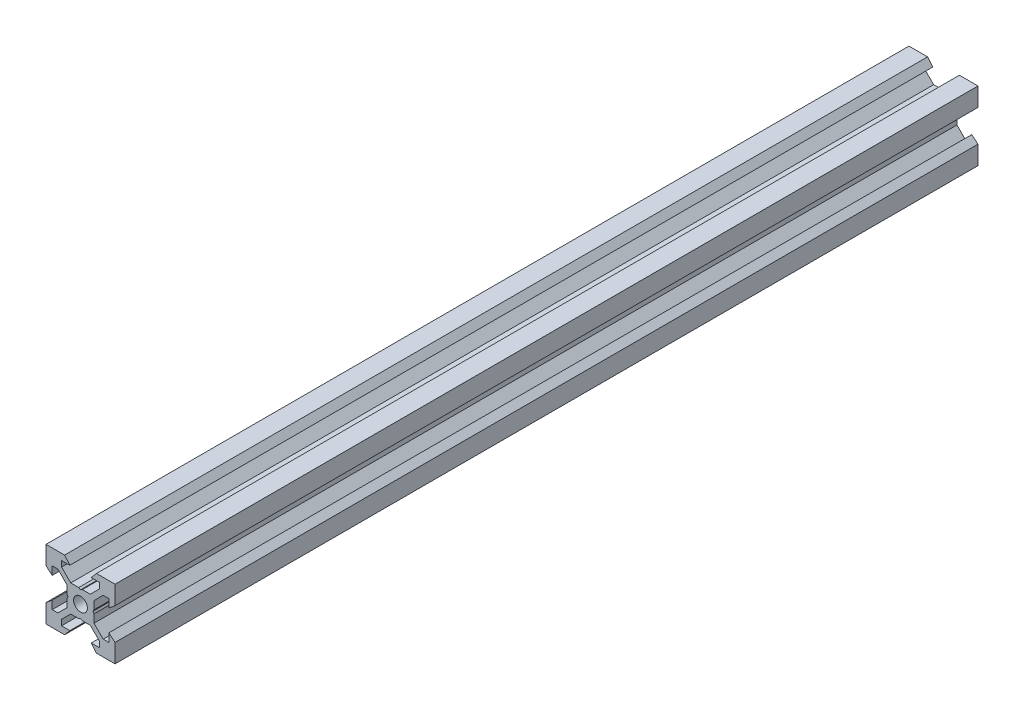
SolidWorks part; units mm, degrees
material "6063-O"
ref_plane "Front Plane" through (0, 0, 0) normal (0, 0, 1) x (1, 0, 0)
ref_plane "Top Plane" through (0, 0, 0) normal (0, 1, 0) x (1, 0, 0)
ref_plane "Right Plane" through (0, 0, 0) normal (1, 0, 0) x (0, 0, -1)
sketch "Sketch1" plane through (0, 0, 0) normal (0, 0, 1) x (1, 0, 0)
  line L0 (10, 10) -> (4.6104, 10) construction
  line L1 (10, 10) -> (10, 4.6104) construction
  line L2 (10, -10) -> (10, -4.6104) construction
  line L3 (10, -10) -> (4.6104, -10) construction
  line L4 (10, 10) -> (10, 4.6104)
  line L5 (6.5607, 5.5) -> (8.2, 5.5)
  line L6 (5.5, 8.2) -> (5.5, 6.5607)
  line L7 (10, 10) -> (4.6104, 10)
  line L8 (10, 10) -> (10, 4.6104)
  line L9 (6.5607, 5.5) -> (3.9, 2.8393)
  line L10 (5.5, 6.5607) -> (2.8393, 3.9)
  line L11 (10, 4.6104) -> (8.2, 3.1)
  line L12 (4.6104, 10) -> (3.1, 8.2)
  line L13 (8.2, 3.1) -> (8.2, 5.5)
  line L14 (3.1, 8.2) -> (5.5, 8.2)
  line L15 (-6.5607, 5.5) -> (-8.2, 5.5)
  line L16 (6.5607, -5.5) -> (8.2, -5.5)
  line L17 (3.1, -8.2) -> (5.5, -8.2)
  line L18 (8.2, -3.1) -> (8.2, -5.5)
  line L19 (4.6104, -10) -> (3.1, -8.2)
  line L20 (10, -4.6104) -> (8.2, -3.1)
  line L21 (0.5196, -3.9) -> (0, -3.6)
  line L22 (0.5196, 3.9) -> (0, 3.6)
  line L23 (3.6, 0) -> (3.9, -0.5196)
  line L24 (3.9, 0.5196) -> (3.6, 0)
  line L25 (3.9, 0.5196) -> (3.9, 2.8393)
  line L26 (2.8393, 3.9) -> (0.5196, 3.9)
  line L27 (3.9, -2.8393) -> (3.9, -0.5196)
  line L28 (2.8393, -3.9) -> (0.5196, -3.9)
  line L29 (5.5, -6.5607) -> (2.8393, -3.9)
  line L30 (6.5607, -5.5) -> (3.9, -2.8393)
  line L31 (10, -10) -> (10, -4.6104)
  line L32 (10, -10) -> (4.6104, -10)
  line L33 (5.5, -8.2) -> (5.5, -6.5607)
  line L34 (-6.5607, -5.5) -> (-8.2, -5.5)
  line L35 (10, -10) -> (10, -4.6104)
  line L36 (0, 0) -> (0, 8.2) construction
  line L37 (-10, -10) -> (-4.6104, -10) construction
  line L38 (-10, -10) -> (-10, -4.6104) construction
  line L39 (-10, 10) -> (-10, 4.6104) construction
  line L40 (-10, 10) -> (-4.6104, 10) construction
  line L41 (-10, -10) -> (-10, -4.6104)
  line L43 (-5.5, -8.2) -> (-5.5, -6.5607)
  line L44 (-10, -10) -> (-4.6104, -10)
  line L45 (-10, -10) -> (-10, -4.6104)
  line L46 (-6.5607, -5.5) -> (-3.9, -2.8393)
  line L47 (-5.5, -6.5607) -> (-2.8393, -3.9)
  line L48 (-2.8393, -3.9) -> (-0.5196, -3.9)
  line L49 (-3.9, -2.8393) -> (-3.9, -0.5196)
  line L50 (-2.8393, 3.9) -> (-0.5196, 3.9)
  line L51 (-3.9, 0.5196) -> (-3.9, 2.8393)
  line L52 (-3.9, 0.5196) -> (-3.6, 0)
  line L53 (-3.6, 0) -> (-3.9, -0.5196)
  line L54 (-0.5196, 3.9) -> (0, 3.6)
  line L55 (-0.5196, -3.9) -> (0, -3.6)
  line L56 (-10, -4.6104) -> (-8.2, -3.1)
  line L57 (-4.6104, -10) -> (-3.1, -8.2)
  line L58 (-8.2, -3.1) -> (-8.2, -5.5)
  line L59 (-3.1, -8.2) -> (-5.5, -8.2)
  line L60 (-10, -10) -> (10, -10) construction
  line L61 (-10, -10) -> (-10, 10) construction
  line L62 (-3.1, 8.2) -> (-5.5, 8.2)
  line L63 (-8.2, 3.1) -> (-8.2, 5.5)
  line L64 (-4.6104, 10) -> (-3.1, 8.2)
  line L65 (-10, 4.6104) -> (-8.2, 3.1)
  line L66 (-5.5, 6.5607) -> (-2.8393, 3.9)
  line L67 (-6.5607, 5.5) -> (-3.9, 2.8393)
  line L68 (-10, 10) -> (-10, 4.6104)
  line L69 (-10, 10) -> (-4.6104, 10)
  line L70 (-5.5, 8.2) -> (-5.5, 6.5607)
  line L71 (-10, 10) -> (10, 10) construction
  line L72 (-10, 10) -> (-10, 4.6104)
  line L73 (10, -10) -> (10, 10) construction
  line L74 (-10, -10) -> (10, 10) construction
  line L75 (-10, 10) -> (10, -10) construction
  circle A0 centre (0, 0) radius 2
  dimension "D7" = 4
  dimension "D1" = 20
  dimension "D2" = 5.3896
  dimension "D3" = 4.5
  dimension "D4" = 50
  dimension "D5" = 1.8
  dimension "D6" = 1.5104
  dimension "D8" = 5.5
  dimension "D9" = 120
  dimension "D10" = 0.3
  dimension "D11" = 2.3197
  dimension "D12" = 7.8
  dimension "D13" = 7.8
  dimension "D14" = 1.5
  dimension "D15" = 2.6607
extrude "Boss-Extrude1" add sketch "Sketch1" along normal mid plane 250 contours L70 L62 L64 L69 L68 L65 L63 L15 L67 L51 L52 L53 L49 L46 L34 L58 L56 L41 L44 L57 L59 L43 L47 L48 L55 L21 L28 L29 L33 L17 L19 L32 L31 L20 L18 L16 L30 L27 L23 L24 L25 L9 L5 L13 L11 L4 L7 L12 L14 L6 L10
